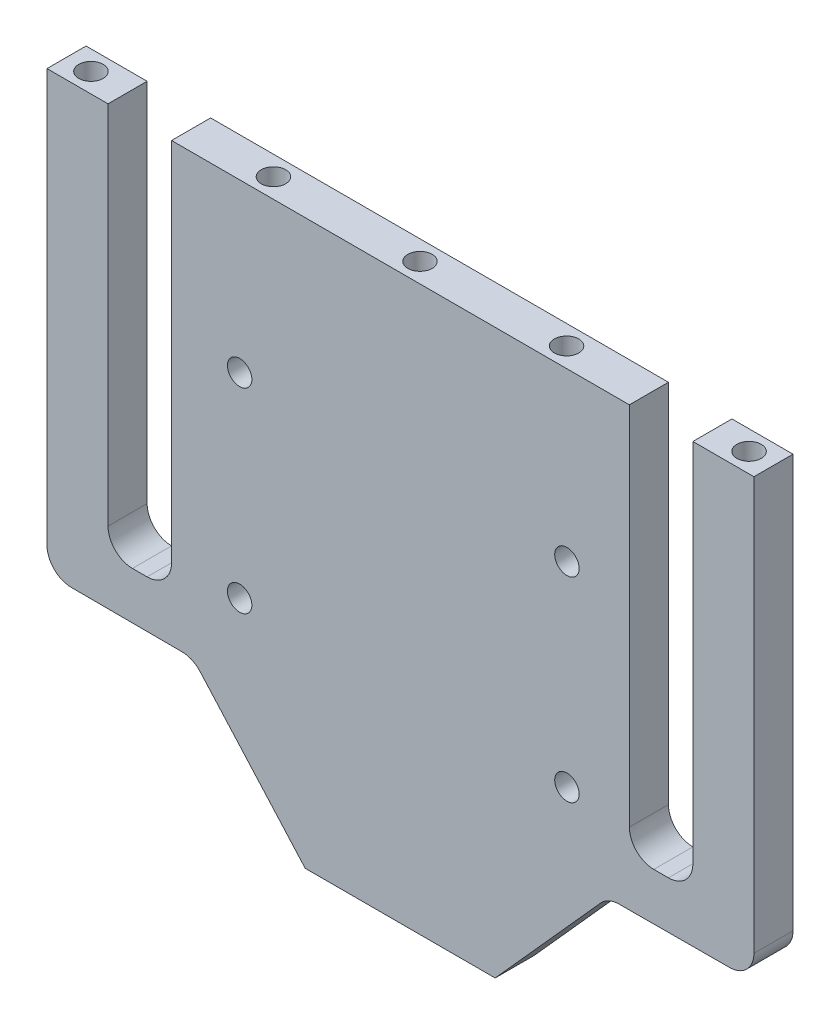
SolidWorks part; units mm, degrees
ref_plane "Front Plane" through (0, 0, 0) normal (0, 0, 1) x (1, 0, 0)
ref_plane "Top Plane" through (0, 0, 0) normal (0, 1, 0) x (1, 0, 0)
ref_plane "Right Plane" through (0, 0, 0) normal (1, 0, 0) x (0, 0, -1)
sketch "Sketch1" plane through (0, 0, 0) normal (0, 0, 1) x (1, 0, 0)
  line L4 (70, 309.9858) -> (85.2992, 309.9858)
  line L6 (43.2101, 271.7903) -> (49.7246, 305.9232)
  line L7 (42.2614, 270.1156) -> (0.0495, 220.7861)
  line L8 (0.0495, 220.7861) -> (42.9, 220.7861) construction
  line L9 (42.9, 220.7861) -> (42.9, 270.8599) construction
  line L10 (96.9829, 220.8599) -> (96.9829, 270.8599) construction
  line L11 (112.4871, 25.7747) -> (89.3829, 25.7747) construction
  line L12 (27.5129, 25.7747) -> (50.5, 25.7747) construction
  line L13 (25.2828, 25.7823) -> (2.6386, 25.8599)
  line L14 (96.6727, 271.7903) -> (90.212, 305.9159)
  line L15 (70, 329.5221) -> (70, -78.2612) construction
  line L18 (50.5, 25.7747) -> (50.5, 0) construction
  line L19 (70, 309.9858) -> (54.636, 309.9858)
  line L20 (135.9829, 220.8599) -> (96.9829, 220.8599) construction
  line L21 (139.9505, 220.7861) -> (135.9829, 220.8599) construction
  line L25 (89.3829, 25.7747) -> (89.3829, 0) construction
  line L27 (89.3829, 0) -> (50.5, 0)
  line L28 (15.1386, 35.4925) -> (18.1386, 35.4925)
  line L35 (124.8614, 35.4925) -> (121.8614, 35.4925)
  line L36 (116.8614, 213.626) -> (129.8614, 213.626)
  line L37 (116.8614, 40.4925) -> (116.8614, 213.626)
  line L38 (129.8614, 213.626) -> (129.8614, 40.4925)
  line L39 (142.3614, 214.274) -> (142.3614, 30.8599)
  line L40 (97.6215, 270.1156) -> (139.9505, 220.7861)
  line L41 (-2.3614, 214.274) -> (-2.3614, 30.8599)
  line L42 (10.1386, 213.626) -> (10.1386, 40.4925)
  line L43 (23.1386, 40.4925) -> (23.1386, 213.626)
  line L44 (23.1386, 213.626) -> (10.1386, 213.626)
  line L45 (28.9972, 24.1103) -> (50.5, 0)
  line L46 (114.7172, 25.7823) -> (137.3614, 25.8599)
  line L47 (89.3829, 0) -> (111.0028, 24.1103)
  arc A1 (42.2614, 270.1156) -> (43.2101, 271.7903) centre (38.4667, 273.3715) ccw
  arc A5 (97.6215, 270.1156) -> (96.6727, 271.7903) centre (101.4161, 273.3715) cw
  arc A8 (137.3614, 25.8599) -> (142.3614, 30.8599) centre (137.3614, 30.8599) ccw
  arc A9 (2.6386, 25.8599) -> (-2.3614, 30.8599) centre (2.6386, 30.8599) cw
  arc A10 (49.7246, 305.9232) -> (54.636, 309.9858) centre (54.636, 304.9858) cw
  arc A11 (85.2992, 309.9858) -> (90.212, 305.9159) centre (85.2992, 304.9858) cw
  arc A12 (139.9505, 220.7861) -> (142.3614, 214.274) centre (132.3614, 214.274) cw
  arc A13 (0.0495, 220.7861) -> (-2.3614, 214.274) centre (7.6386, 214.274) ccw
  arc A14 (25.2828, 25.7823) -> (28.9972, 24.1103) centre (25.2657, 20.7823) cw
  arc A15 (114.7172, 25.7823) -> (111.0028, 24.1103) centre (114.7343, 20.7823) ccw
  arc A16 (121.8614, 35.4925) -> (116.8614, 40.4925) centre (121.8614, 40.4925) cw
  arc A17 (124.8614, 35.4925) -> (129.8614, 40.4925) centre (124.8614, 40.4925) ccw
  arc A18 (15.1386, 35.4925) -> (10.1386, 40.4925) centre (15.1386, 40.4925) cw
  arc A19 (18.1386, 35.4925) -> (23.1386, 40.4925) centre (18.1386, 40.4925) ccw
  point P18 (116.8614, 35.4925)
  point P51 (129.8614, 35.4925)
  point P59 (10.1386, 35.4925)
  point P62 (23.1386, 35.4925)
  dimension "D1" = 5
  dimension "D2" = 5
  dimension "D3" = 5
  dimension "D4" = 10
  dimension "D5" = 5
  dimension "D6" = 5
extrude "Boss-Extrude1" add sketch "Sketch1" along normal blind 8
sketch "Sketch2" plane through (0, 0, 8) normal (0, 0, 1) x (1, 0, 0)
  line L2 (92.3829, 206.0089) -> (47.3829, 206.0089)
  line L8 (47.3829, 206.0089) -> (47.3829, 154.0089)
  line L9 (47.3829, 154.0089) -> (92.3829, 154.0089)
  line L10 (92.3829, 206.0089) -> (92.3829, 154.0089)
extrude "Cut-Extrude1" cut sketch "Sketch2" against normal through all contours L10 L2 L8 L9
sketch "Sketch3" plane through (0, 0, 0) normal (0, 0, -1) x (-1, 0, 0)
  line L1 (-142.3614, 115.3599) -> (2.3614, 115.3599)
  line L3 (-142.3614, 30.8599) -> (-142.3614, 214.274) construction
  line L6 (2.3614, 214.274) -> (2.3614, 30.8599) construction
split "Split1" trim tools "Sketch3" bodies to split 102 resulting bodies 104 108
ref_plane "Plane4" through (0, 115.3599, 0) normal (0, 1, 0) x (1, 0, 0)
sketch "Sketch4" plane through (0, 115.3599, 0) normal (0, -1, 0) x (-1, 0, 0)
  line L0 (-3.8886, -8) -> (-3.8886, -4)
  line L2 (2.3614, -8) -> (-10.1386, -8) construction
  circle A1 centre (-70, -4) radius 2.5
  circle A2 centre (-40, -4) radius 2.5
  circle A3 centre (-100, -4) radius 2.5
  circle A5 centre (-137.3614, -4) radius 2.5
  circle A6 centre (-3.8886, -4) radius 2.5
sketch "Sketch5" plane through (0, 115.3599, -115.3599) normal (0, -1, 0) x (1, 0, 0)
  circle A1 centre (70, 119.3599) radius 2.5
  circle A2 centre (100, 119.3599) radius 2.5
  circle A3 centre (40, 119.3599) radius 2.5
  circle A5 centre (2.6386, 119.3599) radius 2.5
  circle A6 centre (137.3614, 119.3599) radius 2.5
extrude "Cut-Extrude6" cut sketch "Sketch5" along direction (0, -1, 0) on the side of the normal blind 10 contours A2 | A5 | A3 | A1 | A6
extrude "Cut-Extrude7" cut sketch "Sketch4" against normal blind 5.2 contours A2 | A6 | A1 | A3 | A5
delete or keep bodies "Body-Delete/Keep 3" type delete bodies bodies 107
sketch "Sketch6" plane through (0, 0, 8) normal (0, 0, 1) x (1, 0, 0)
  circle A0 centre (37.0786, 81.1925) radius 2.5
  circle A1 centre (104.0786, 81.1925) radius 2.5
  circle A2 centre (104.0786, 41.1925) radius 2.5
  circle A3 centre (37.0786, 41.1925) radius 2.5
extrude "Cut-Extrude8" cut sketch "Sketch6" against normal through all
